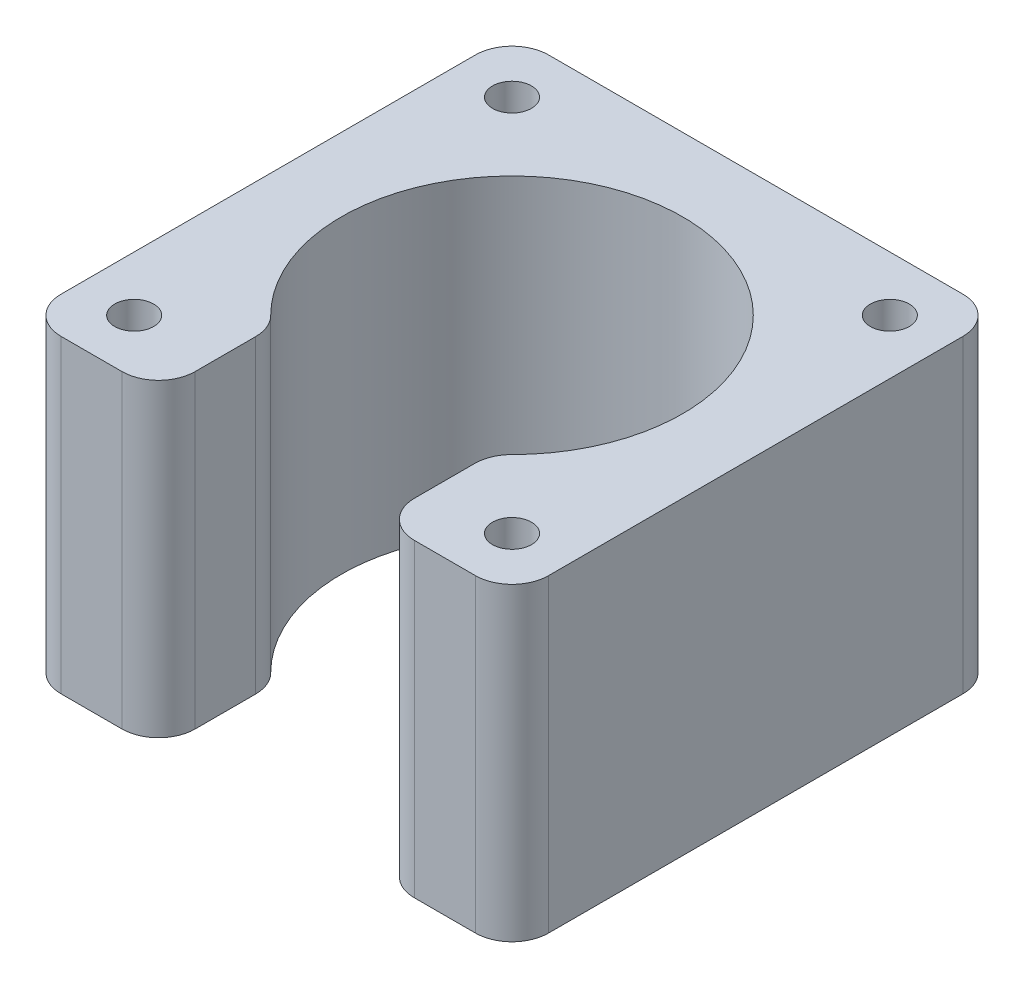
SolidWorks part; units mm, degrees
material "ABS"
ref_plane "Front Plane" through (0, 0, 0) normal (0, 0, 1) x (1, 0, 0)
ref_plane "Top Plane" through (0, 0, 0) normal (0, 1, 0) x (1, 0, 0)
ref_plane "Right Plane" through (0, 0, 0) normal (1, 0, 0) x (0, 0, -1)
sketch "Sketch1" plane through (0, 0, 0) normal (0, 1, 0) x (1, 0, 0)
  line L0 (-20, -20) -> (-9, -20)
  line L1 (-9, -20) -> (-9, -10.7238)
  line L3 (9, -10.7238) -> (9, -20)
  line L4 (9, -20) -> (20, -20)
  line L5 (20, -20) -> (20, 20)
  line L6 (20, 20) -> (-20, 20)
  line L7 (-20, 20) -> (-20, -20)
  line L8 (0, 0) -> (0, 15.5) construction
  line L9 (-15.5, 15.5) -> (15.5, 15.5) construction
  line L10 (-15.5, 15.5) -> (-15.5, -15.5) construction
  line L11 (-15.5, -15.5) -> (15.5, -15.5) construction
  line L12 (15.5, 15.5) -> (15.5, -15.5) construction
  circle A0 centre (-15.5, -15.5) radius 1.5 construction
  circle A1 centre (15.5, -15.5) radius 1.5 construction
  circle A2 centre (15.5, 15.5) radius 1.5 construction
  circle A3 centre (-15.5, 15.5) radius 1.5 construction
  arc A4 (9, -10.7238) -> (-9, -10.7238) centre (0, 0) ccw
  circle A5 centre (-25, 0) radius 1.5 construction
  arc A6 (-20, 10) -> (-20, -10) centre (-20, 0) ccw construction
  arc A9 (10, 20) -> (-10, 20) centre (0, 20) ccw construction
  circle A10 centre (0, 25) radius 1.5 construction
  arc A11 (20, -10) -> (20, 10) centre (20, 0) ccw construction
  circle A12 centre (25, 0) radius 1.5 construction
  point P25 (15.5, 0)
  point P26 (20, 0)
  point P39 (0, 0)
  dimension "D3" = 3
  dimension "D4" = 14
  dimension "D5" = 5
  dimension "D6" = 3
  dimension "D7" = 20
  dimension "D1" = 31
  dimension "D2" = 40
  dimension "D8" = 18
  dimension "D9" = 3
extrude "Boss-Extrude1" add sketch "Sketch1" against normal blind 25.4
hole_wizard "M3 Clearance Hole1" positions "3DSketch1" profile "Sketch2" hole size "M3" standard "ANSI Metric" end condition through all
sketch3d "3DSketch1"
  point P41 (-15.5, 0, -15.5)
  point P43 (15.5, 0, -15.5)
  point P45 (15.5, 0, 15.5)
  point P47 (-15.5, 0, 15.5)
sketch "Sketch2" plane through (-15.5, 0, -15.5) normal (1, 0, 0) x (0, 0, 1)
  line L0 (0, 0) -> (0, 25.4)
  line L1 (0, 25.4) -> (1.6, 25.4)
  line L2 (1.6, 25.4) -> (1.6, 0)
  line L5 (1.6, 0) -> (0, 0)
  line L11 (0, -6.35) -> (0, 107.95) construction
  dimension "Thru Hole Dia." = 3.2
  dimension "Thru Hole Depth" = 25.4
fillet "Fillet1" radius 3 8 edges at (-9, -12.7, 20) (9, -12.7, 20) (9, -12.7, 10.7238) (-9, -12.7, 10.7238) (-20, -12.7, -20) (20, -12.7, -20) (20, -12.7, 20) (-20, -12.7, 20)
